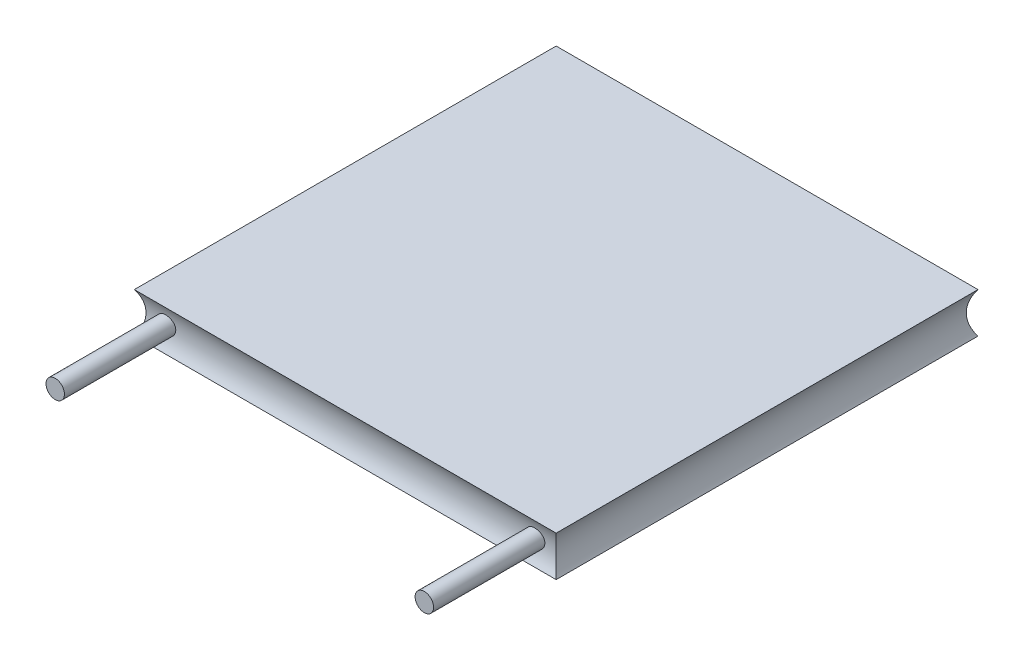
SolidWorks part; units mm, degrees
material "Ceramic Porcelain"
ref_plane "Front Plane" through (0, 0, 0) normal (0, 0, 1) x (1, 0, 0)
ref_plane "Top Plane" through (0, 0, 0) normal (0, 1, 0) x (1, 0, 0)
ref_plane "Right Plane" through (0, 0, 0) normal (1, 0, 0) x (0, 0, -1)
sketch "Sketch1" plane through (0, 0, 0) normal (0, 1, 0) x (1, 0, 0)
  line L1 (0, 0) -> (40, 0)
  line L2 (0, 0) -> (0, 40)
  line L3 (0, 40) -> (40, 40)
  line L4 (40, 0) -> (40, 40)
extrude "Boss-Extrude1" add sketch "Sketch1" along normal blind 3.82
sketch "Sketch2" plane through (0, 0, 0) normal (0, 0, 1) x (1, 0, 0)
  line L0 (0, 1.91) -> (-3, 1.91)
  line L1 (0, 3.82) -> (0, 0) construction
  line L2 (0, 0) -> (40, 0) construction
  line L3 (0, 3.82) -> (-3, 1.91)
  line L4 (0, 0) -> (-3, 1.91)
  line L5 (40, 1.91) -> (43, 1.91)
  line L6 (40, 3.82) -> (40, 0) construction
  line L7 (40, 3.82) -> (43, 1.91)
  line L8 (40, 0) -> (43, 1.91)
  arc A0 (0, 3.82) -> (0, 0) centre (-3, 1.91) cw
  arc A1 (40, 3.82) -> (40, 0) centre (43, 1.91) ccw
  line M6 (40, 0) -> (40, 3.82)
  line M8 (0, 3.82) -> (0, 0)
extrude "Cut-Extrude2" cut sketch "Sketch2" against normal through all contours L3 L0 M8 | A0 M8 | L4 L0 M8 | L7 L5 M6 | L8 L5 M6 | A1 M6
sketch "Sketch3" plane through (0, 0, 0) normal (1, 0, 0) x (0, 0, -1)
  line L0 (40, 1.91) -> (43, 1.91)
  line L1 (40, 0) -> (40, 3.82) construction
  line L2 (0, 1.91) -> (-3, 1.91)
  line L3 (0, 3.82) -> (0, 0) construction
  line L4 (40, 3.82) -> (43, 1.91)
  line L5 (40, 0) -> (43, 1.91)
  line L6 (0, 3.82) -> (-3, 1.91)
  line L7 (0, 0) -> (-3, 1.91)
  arc A0 (0, 3.82) -> (0, 0) centre (-3, 1.91) cw
  arc A1 (40, 3.82) -> (40, 0) centre (43, 1.91) ccw
extrude "Cut-Extrude5" cut sketch "Sketch3" along normal blind 45
sketch "Sketch4" plane through (0, 0, 0) normal (0, 0, 1) x (1, 0, 0)
  circle A0 centre (2.5, 1.91) radius 0.875
extrude "Boss-Extrude2" add sketch "Sketch4" along normal blind 10 and the other way blind 5
sketch "Sketch5" plane through (0, 0, 0) normal (0, 0, 1) x (1, 0, 0)
  circle A0 centre (37.5, 1.91) radius 0.875
extrude "Boss-Extrude3" add sketch "Sketch5" along normal blind 10 and the other way blind 5
ref_plane "Plane1" through (0, 0, -20) normal (0, 0, 1) x (1, 0, 0)
ref_plane "Plane2" through (20, 0, 0) normal (1, 0, 0) x (0, 0, -1)
